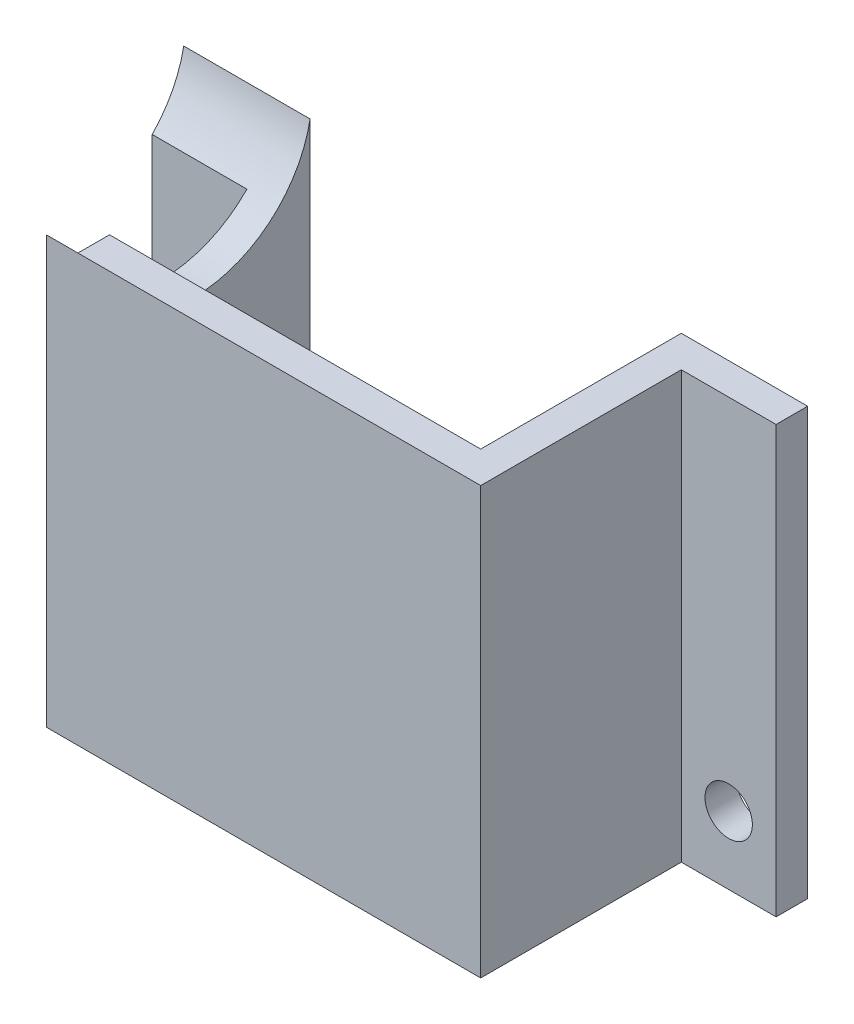
SolidWorks part; units mm, degrees
ref_plane "Front Plane" through (0, 0, 0) normal (0, 0, 1) x (1, 0, 0)
ref_plane "Top Plane" through (0, 0, 0) normal (0, 1, 0) x (1, 0, 0)
ref_plane "Right Plane" through (0, 0, 0) normal (1, 0, 0) x (0, 0, -1)
sketch "Sketch1" plane through (0, 0, 0) normal (0, 0, 1) x (1, 0, 0)
  line L0 (-10.2057, 6.7823) -> (-10.2057, -6.7177)
  line L1 (-5.0057, -6.7177) -> (13.2943, -6.7177)
  line L2 (13.2943, -6.7177) -> (13.2943, 6.7823)
  line L3 (13.2943, 6.7823) -> (21.2943, 6.7823)
  line L4 (21.2943, 6.7823) -> (21.2943, -20.2177)
  line L5 (21.2943, -20.2177) -> (-18.2057, -20.2177)
  line L6 (-18.2057, -20.2177) -> (-18.2057, 6.7823)
  line L7 (-18.2057, 6.7823) -> (-10.2057, 6.7823)
  line L9 (-8.2057, -12.2177) -> (-5.0057, -12.2177)
  line L10 (-5.0057, -12.2177) -> (-5.0057, -6.7177)
  line L11 (-10.2057, -6.7177) -> (-8.2057, -6.7177)
  line L12 (-8.2057, -6.7177) -> (-8.2057, -12.2177)
  dimension "D1" = 13.5
  dimension "D2" = 8
  dimension "D3" = 8
  dimension "D4" = 5.5
  dimension "D5" = 13.5
  dimension "D6" = 8
  dimension "D7" = 27
  dimension "D8" = 23.5
  dimension "D9" = 2
  dimension "D10" = 3.2
extrude "Boss-Extrude1" add sketch "Sketch1" along normal blind 12.7
sketch "Sketch2" plane through (0, 0, 12.7) normal (0, 0, 1) x (1, 0, 0)
  line L1 (-18.2057, 6.7823) -> (21.2943, 6.7823)
  line L2 (-18.2057, 6.7823) -> (-18.2057, -20.2177)
  line L3 (-18.2057, -20.2177) -> (21.2943, -20.2177)
  line L4 (21.2943, 6.7823) -> (21.2943, -20.2177)
extrude "Boss-Extrude2" add sketch "Sketch2" along normal blind 2
sketch "Sketch3" plane through (0, 6.7823, 0) normal (0, 1, 0) x (1, 0, 0)
  line L0 (-18.2057, -14.7) -> (-12.2057, -14.7)
  line L2 (-18.2057, -14.7) -> (-18.2057, 0) construction
  line L3 (-12.2057, -14.7) -> (-12.2057, -2)
  line L5 (-12.2057, -2) -> (-18.2057, -2)
  line L6 (-18.2057, -2) -> (-18.2057, -14.7)
  line L8 (21.2943, -14.7) -> (-18.2057, -14.7) construction
  line L10 (15.2943, -2) -> (21.2943, -2)
  line L11 (15.2943, -14.7) -> (15.2943, -2)
  line L12 (21.2943, -14.7) -> (15.2943, -14.7)
  line L13 (21.2943, -2) -> (21.2943, -14.7)
  line L14 (13.2943, -12.7) -> (13.2943, 0) construction
  line L15 (-10.2057, 0) -> (-18.2057, 0) construction
  line L16 (21.2943, 0) -> (13.2943, 0) construction
  line L17 (21.2943, -14.7) -> (21.2943, 0) construction
  line L18 (-10.2057, -12.7) -> (-10.2057, 0) construction
  point P23 (-12.2057, 0)
  dimension "D1" = 2
  dimension "D2" = 0
  dimension "D3" = 2
  dimension "D4" = 2
  dimension "D5" = 0
  dimension "D6" = 2
  dimension "D7" = 0
extrude "Cut-Extrude1" cut sketch "Sketch3" against normal through all
sketch "Sketch4" plane through (-12.2057, 0, 0) normal (-1, 0, 0) x (0, 0, 1)
  line L0 (6.371, 6.7823) -> (6.371, 0.7823) construction
  line L1 (14.7, 6.7823) -> (2, 6.7823) construction
  line L2 (0, 6.7823) -> (14.7, 6.7823)
  arc A0 (0, 6.7823) -> (14.7, 6.7823) centre (7.35, 8.1569) ccw
  dimension "D1" = 6
extrude "Cut-Extrude2" cut sketch "Sketch4" along normal blind 12 from surface at -2 starting at face at (-10.2057, 0.0323, 6.35)
sketch "Sketch5" plane through (0, 0, 0) normal (0, 0, -1) x (-1, 0, 0)
  line L0 (-21.2943, -20.2177) -> (-21.2943, 6.7823) construction
  line L1 (18.2057, 6.7823) -> (18.2057, -20.2177) construction
  circle A0 centre (-18.2943, -15.9174) radius 1.5
  circle A1 centre (15.2057, -15.9174) radius 1.5
  dimension "D1" = 3
  dimension "D2" = 3
  dimension "D3" = 3
  dimension "D4" = 3
extrude "Cut-Extrude3" cut sketch "Sketch5" against normal through all
